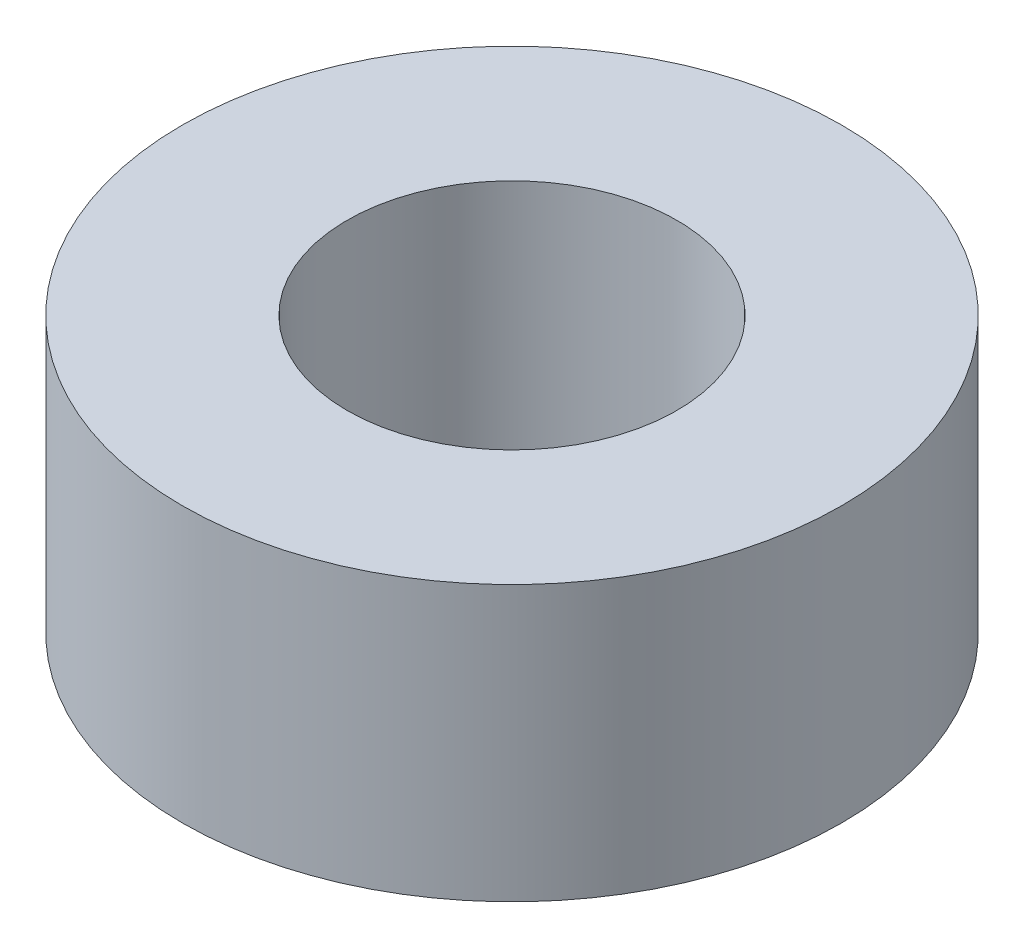
SolidWorks part; units mm, degrees
material "合金钢"
ref_plane "前视基准面" through (0, 0, 0) normal (0, 0, 1) x (1, 0, 0)
ref_plane "上视基准面" through (0, 0, 0) normal (0, 1, 0) x (1, 0, 0)
ref_plane "右视基准面" through (0, 0, 0) normal (1, 0, 0) x (0, 0, -1)
sketch "草图1" plane through (0, 0, 0) normal (0, 1, 0) x (1, 0, 0)
  circle A0 centre (0, 0) radius 3
  circle A1 centre (0, 0) radius 1.5
  dimension "D1" = 6
  dimension "D2" = 3
extrude "凸台-拉伸1" add sketch "草图1" along normal blind 2.5
